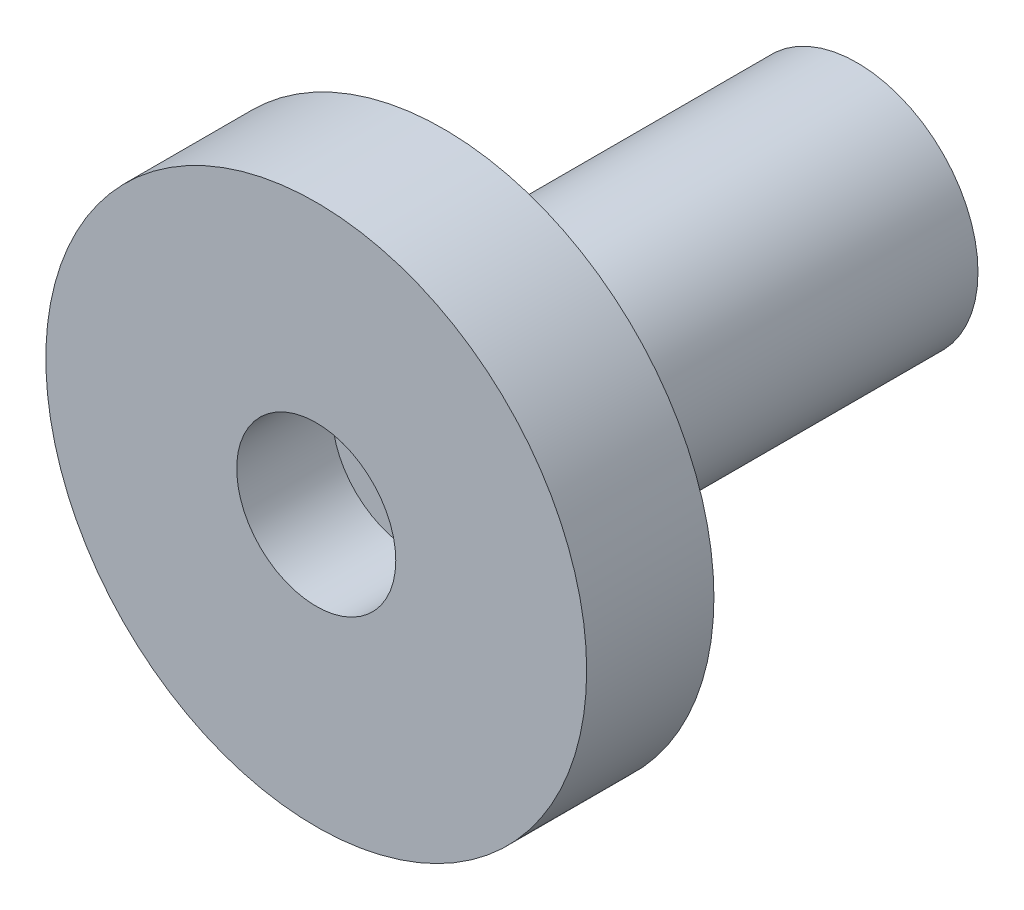
SolidWorks part; units mm, degrees
ref_plane "Front Plane" through (0, 0, 0) normal (0, 0, 1) x (1, 0, 0)
ref_plane "Top Plane" through (0, 0, 0) normal (0, 1, 0) x (1, 0, 0)
ref_plane "Right Plane" through (0, 0, 0) normal (1, 0, 0) x (0, 0, -1)
sketch "Sketch1" plane through (0, 0, 0) normal (0, 0, 1) x (1, 0, 0)
  circle A0 centre (-58.8, 0) radius 3.8
  circle A1 centre (-58.8, 0) radius 1.6
extrude "Boss-Extrude1" add sketch "Sketch1" along normal blind 5 and the other way blind 8
sketch "Sketch2" plane through (0, 0, 5) normal (0, 0, 1) x (1, 0, 0)
  circle A0 centre (-58.8, 0) radius 8.5
extrude "Boss-Extrude2" add sketch "Sketch2" along normal blind 4
sketch "Sketch4" plane through (0, 0, 5) normal (0, 0, -1) x (-1, 0, 0)
  circle A1 centre (58.8, 0) radius 1.6
  circle A2 centre (58.8, 0) radius 1.6
  dimension "D1" = 0
extrude "Cut-Extrude1" cut sketch "Sketch4" against normal blind 4
sketch "Sketch5" plane through (0, 0, 9) normal (0, 0, 1) x (1, 0, 0)
  circle A0 centre (-58.8, 0) radius 2.5
extrude "Cut-Extrude2" cut sketch "Sketch5" against normal blind 3
